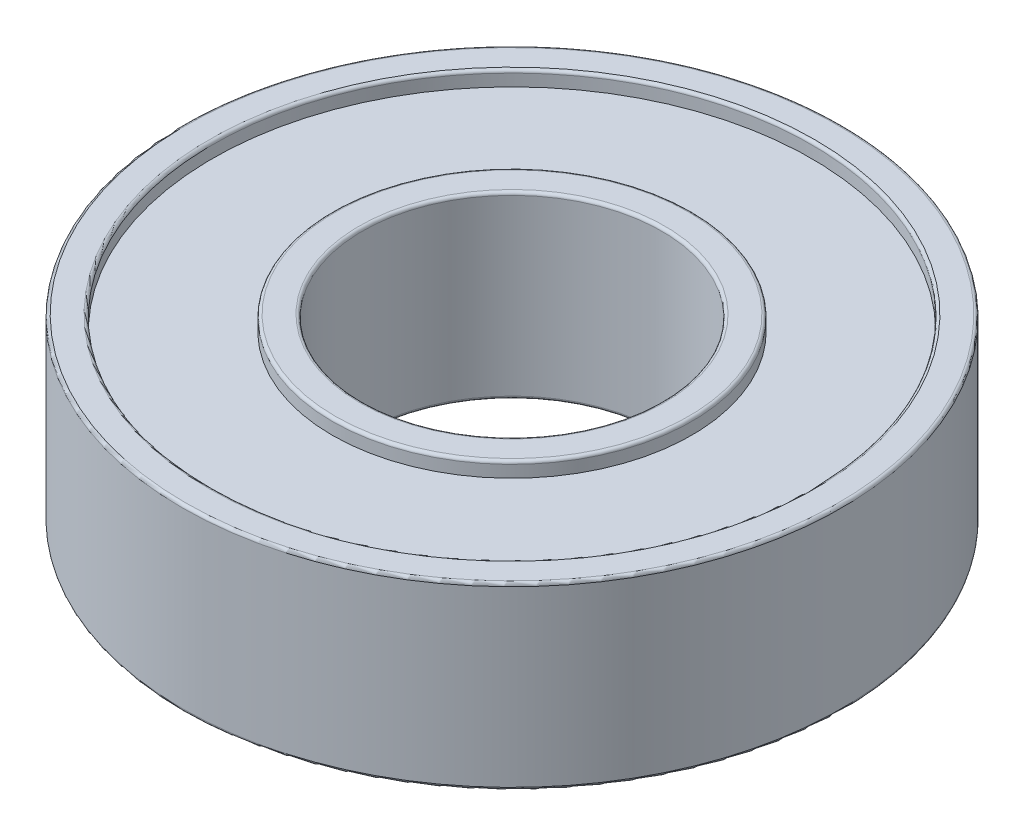
SolidWorks part; units mm, degrees
material "AISI 1045 钢，冷拔"
ref_plane "前视基准面" through (0, 0, 0) normal (0, 0, 1) x (1, 0, 0)
ref_plane "上视基准面" through (0, 0, 0) normal (0, 1, 0) x (1, 0, 0)
ref_plane "右视基准面" through (0, 0, 0) normal (1, 0, 0) x (0, 0, -1)
ref_plane "基准面1" through (0, 0, 0) normal (0, 0, -1) x (-1, 0, 0)
sketch "草图1" plane through (0, 0, 0) normal (0, 0, -1) x (-1, 0, 0)
  line L0 (-5.1, 3) -> (-5.9, 3)
  line L1 (-6, 2.9) -> (-6, 2.5)
  line L2 (-6, 2.5) -> (-10, 2.5)
  line L3 (-10, 2.5) -> (-10, 2.9)
  line L4 (-10.1, 3) -> (-10.9, 3)
  line L5 (-11, 2.9) -> (-11, -2.9)
  line L6 (-10.9, -3) -> (-10.1, -3)
  line L7 (-10, -2.9) -> (-10, -2.5)
  line L8 (-10, -2.5) -> (-6, -2.5)
  line L9 (-6, -2.5) -> (-6, -2.9)
  line L10 (-5.9, -3) -> (-5.1, -3)
  line L11 (-5, -2.9) -> (-5, 2.9)
  line L12 (0, -3) -> (0, 3) construction
  arc A0 (-5.9, 3) -> (-6, 2.9) centre (-5.9, 2.9) ccw
  arc A1 (-10, 2.9) -> (-10.1, 3) centre (-10.1, 2.9) ccw
  arc A2 (-10.9, 3) -> (-11, 2.9) centre (-10.9, 2.9) ccw
  arc A3 (-11, -2.9) -> (-10.9, -3) centre (-10.9, -2.9) ccw
  arc A4 (-10.1, -3) -> (-10, -2.9) centre (-10.1, -2.9) ccw
  arc A5 (-6, -2.9) -> (-5.9, -3) centre (-5.9, -2.9) ccw
  arc A6 (-5.1, -3) -> (-5, -2.9) centre (-5.1, -2.9) ccw
  arc A7 (-5, 2.9) -> (-5.1, 3) centre (-5.1, 2.9) ccw
revolve "旋转1" add sketch "草图1" angle 360 about L12
